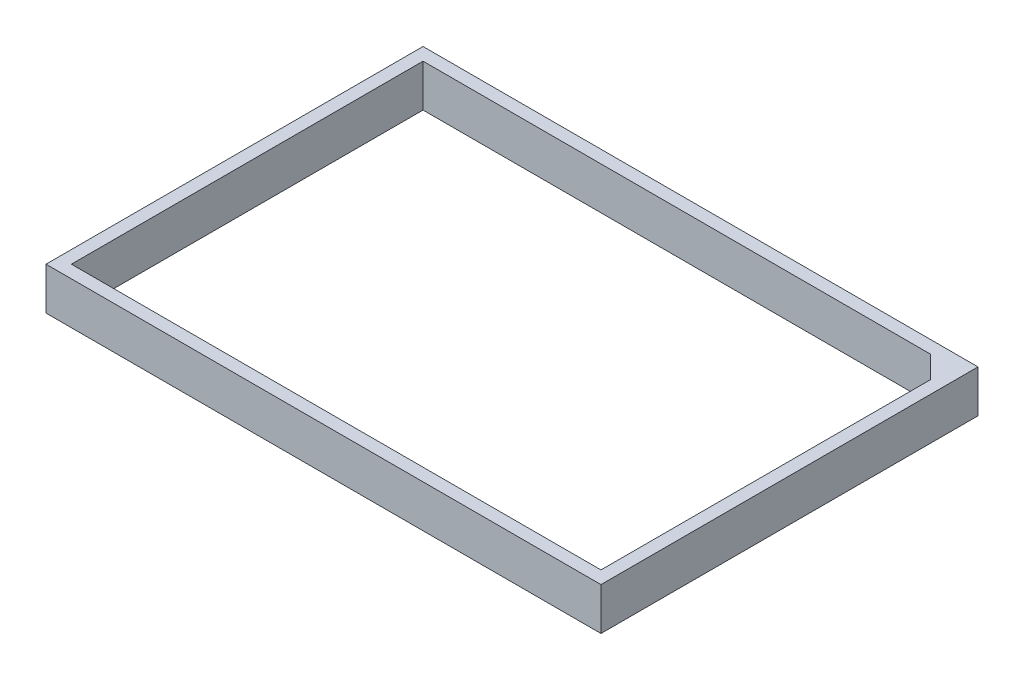
SolidWorks part; units mm, degrees
ref_plane "前视基准面" through (0, 0, 0) normal (0, 0, 1) x (1, 0, 0)
ref_plane "上视基准面" through (0, 0, 0) normal (0, 1, 0) x (1, 0, 0)
ref_plane "右视基准面" through (0, 0, 0) normal (1, 0, 0) x (0, 0, -1)
sketch "Sketch1" plane through (0, 0, 0) normal (0, 1, 0) x (1, 0, 0)
  line L1 (-65.5, 44.5) -> (65.5, 44.5)
  line L2 (-65.5, 44.5) -> (-65.5, -44.5)
  line L3 (-65.5, -44.5) -> (65.5, -44.5)
  line L4 (65.5, 44.5) -> (65.5, -44.5)
  line L5 (-65.5, 44.5) -> (65.5, -44.5) construction
  line L6 (-65.5, -44.5) -> (65.5, 44.5) construction
  point P0 (0, 0)
  dimension "D1" = 131
  dimension "D2" = 89
extrude "Boss-Extrude1" add sketch "Sketch1" along normal blind 10
sketch "Sketch2" plane through (0, 10, 0) normal (0, 1, 0) x (1, 0, 0)
  line L0 (-65.5, 44.5) -> (-65.5, -44.5) construction
  line L2 (-62.2, 41.2) -> (-62.2, -41.2)
  line L3 (-62.2, -41.2) -> (62.2, -41.2)
  line L5 (-62.2, 41.2) -> (62.2, -41.2) construction
  line L6 (-62.2, -41.2) -> (62.2, 41.2) construction
  line L8 (57.2, 41.2) -> (62.2, 36.2)
  line L9 (-62.2, 41.2) -> (57.2, 41.2)
  line L10 (62.2, -41.2) -> (62.2, 36.2)
  line L16 (62.5, -41.5) -> (62.5, 36.3243)
  line L17 (57.3243, 41.5) -> (62.5, 36.3243)
  line L18 (-62.5, 41.5) -> (57.3243, 41.5)
  line L19 (-62.5, 41.5) -> (-62.5, -41.5)
  line L20 (-62.5, -41.5) -> (62.5, -41.5)
  point P0 (0, 0)
  dimension "D1" = 3.3
  dimension "D2" = 0.3
  dimension "D3" = 5
  dimension "D4" = 5
extrude "Cut-Extrude1" cut sketch "Sketch2" against normal blind 100 contours L3 L10 L8 L9 L2 | L19 L20 L16 L17 L18 L10 L3 L2 L9 L8
